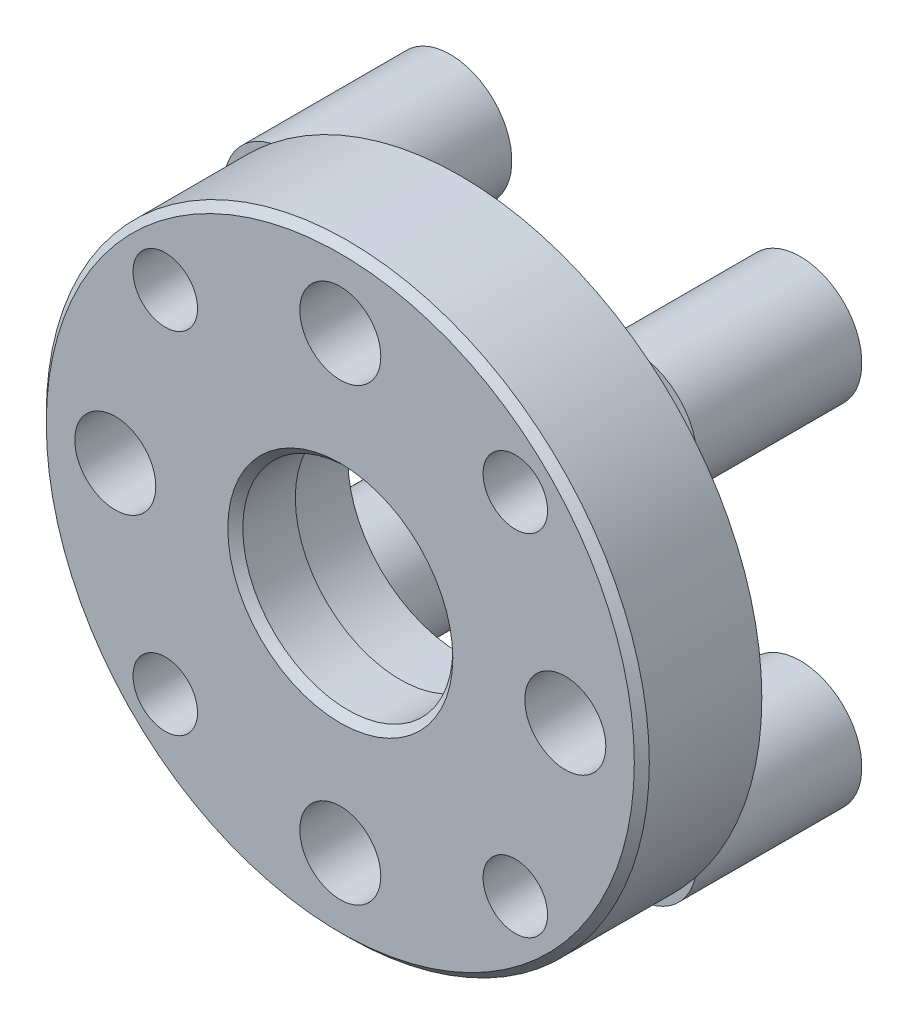
SolidWorks part; units mm, degrees
material "ABS"
ref_plane "Front Plane" through (0, 0, 0) normal (0, 0, 1) x (1, 0, 0)
ref_plane "Top Plane" through (0, 0, 0) normal (0, 1, 0) x (1, 0, 0)
ref_plane "Right Plane" through (0, 0, 0) normal (1, 0, 0) x (0, 0, -1)
ref_plane "Output Plane" through (0, 0, -116.7579) normal (0, 0, -1) x (-1, 0, 0)
sketch "CYC Output Sketch" plane through (0, 0, -116.7579) normal (0, 0, 1) x (1, 0, 0)
  line L1 (11.6673, 11.6673) -> (-11.6673, 11.6673) construction
  line L2 (-11.6673, 11.6673) -> (-11.6673, -11.6673) construction
  line L3 (-11.6673, -11.6673) -> (11.6673, -11.6673) construction
  line L4 (11.6673, -11.6673) -> (11.6673, 11.6673) construction
  circle A0 centre (0, 0) radius 16.5 construction
sketch "Sketch3" plane through (0, 0, -116.7579) normal (0, 0, -1) x (-1, 0, 0)
  circle A0 centre (-11.6673, 11.6673) radius 4
  circle A1 centre (11.6673, 11.6673) radius 4
  circle A2 centre (11.6673, -11.6673) radius 4
  circle A3 centre (-11.6673, -11.6673) radius 4
  dimension "D1" = 8
extrude "Boss-Extrude1" add sketch "Sketch3" along normal blind 11
sketch "Sketch6" plane through (0, 0, -116.7579) normal (0, 0, 1) x (1, 0, 0)
  arc A0 (10.7357, 16.9928) -> (-16.9928, 10.7357) centre (0, 0) ccw
  arc A18 (16.9928, -10.7357) -> (10.7357, 16.9928) centre (0, 0) ccw
  arc A19 (-10.7357, -16.9928) -> (16.9928, -10.7357) centre (0, 0) ccw
  arc A20 (-16.9928, 10.7357) -> (-10.7357, -16.9928) centre (0, 0) ccw
  circle A23 centre (0, 0) radius 7.5
  dimension "D2" = 40.2
  dimension "D1" = 15
extrude "Boss-Extrude6" add sketch "Sketch6" along normal blind 8 contours A23 | A0 A20 A19 A18
sketch "Sketch8" plane through (0, 0, -108.7579) normal (0, 0, 1) x (1, 0, 0)
  line L0 (0, 0) -> (11.6673, 11.6673) construction
  line L1 (0, 0) -> (16.5, 0) construction
  circle A0 centre (0, 0) radius 16.5 construction
  circle A1 centre (11.6673, 11.6673) radius 1.6
  circle A2 centre (11.6673, -11.6673) radius 1.6
  circle A3 centre (-11.6673, -11.6673) radius 1.6
  circle A4 centre (-11.6673, 11.6673) radius 1.6
  point P16 (0, 0)
  dimension "D1" = 33
  dimension "D2" = 45
  dimension "D3" = 3.2
  dimension "D4" = 4
extrude "Cut-Extrude1" cut sketch "Sketch8" against normal through all
sketch "Sketch9" plane through (0, 0, -127.7579) normal (0, 0, 1) x (1, 0, 0)
  circle A0 centre (11.6673, 11.6673) radius 3
  circle A1 centre (11.6673, -11.6673) radius 3
  circle A2 centre (-11.6673, -11.6673) radius 3
  circle A3 centre (-11.6673, 11.6673) radius 3
  point P12 (0, 0)
  dimension "D1" = 6
  dimension "D2" = 4
extrude "Cut-Extrude2" cut sketch "Sketch9" along normal blind 3 from surface at 0 starting at face at (13.2673, 11.6673, -127.7579)
sketch "Sketch10" plane through (0, 0, -127.7579) normal (0, 0, -1) x (-1, 0, 0)
  circle A0 centre (11.6673, 11.6673) radius 4.1
  circle A1 centre (11.6673, 11.6673) radius 4
  circle A2 centre (11.6673, -11.6673) radius 4
  circle A3 centre (11.6673, -11.6673) radius 4.1
  circle A4 centre (-11.6673, -11.6673) radius 4
  circle A5 centre (-11.6673, -11.6673) radius 4.1
  circle A6 centre (-11.6673, 11.6673) radius 4
  circle A7 centre (-11.6673, 11.6673) radius 4.1
  point P16 (0, 0)
  dimension "D1" = 8
  dimension "D2" = 8.2
  dimension "D3" = 4
extrude "Boss-Extrude8" add sketch "Sketch10" against normal blind 11
sketch "Sketch11" plane through (0, 0, -108.7579) normal (0, 0, 1) x (1, 0, 0)
  line L0 (0, 0) -> (0, 15) construction
  circle A0 centre (0, 15) radius 2.7
  circle A1 centre (15, 0) radius 2.7
  circle A2 centre (0, -15) radius 2.7
  circle A3 centre (-15, 0) radius 2.7
  circle A4 centre (-11.6673, 11.6673) radius 2.15
  circle A5 centre (11.6673, 11.6673) radius 2.15
  circle A6 centre (11.6673, -11.6673) radius 2.15
  circle A7 centre (-11.6673, -11.6673) radius 2.15
  point P13 (0, 0)
  dimension "D2" = 5.4
  dimension "D4" = 4.3
  dimension "D1" = 15
  dimension "D3" = 4
extrude "Cut-Extrude3" cut sketch "Sketch11" against normal blind 8
sketch "Sketch12" plane through (0, 0, -108.7579) normal (0, 0, 1) x (1, 0, 0)
  circle A0 centre (0, 0) radius 7.5
  circle A1 centre (0, 0) radius 7
  dimension "D1" = 15
  dimension "D2" = 14
extrude "Boss-Extrude9" add sketch "Sketch12" against normal blind 4
chamfer "Chamfer1" distance 0.5 angle 45 2 edges at (7, 0, -108.7579) (20.1, 0, -108.7579)
equation "\"RingPinShaft\"= 5.05"
equation "\"CenterBearingOut\"=32.00"
equation "\"RingPostIn\"=5.15"
equation "\"CamBearingOut\"=15.1"
equation "\"DiskOutputShaft\"=10.1"
equation "\"CenterShaft\"=25.2"
equation "\"Eccentricity\"=2"
equation "\"CycCamShaft\"=10.05"
equation "\"D2@Sketch6\"=\"OutputBearing\""
equation "\"OutputBearing\"=40.2"
